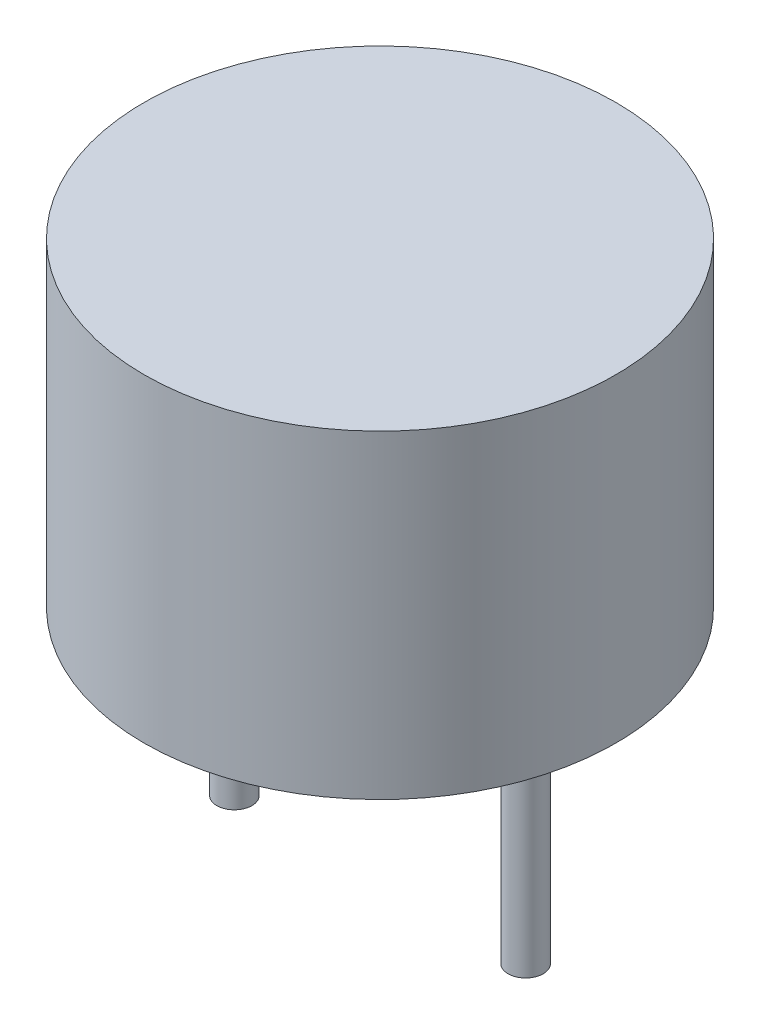
SolidWorks part; units mm, degrees
ref_plane "Front Plane" through (0, 0, 0) normal (0, 0, 1) x (1, 0, 0)
ref_plane "Top Plane" through (0, 0, 0) normal (0, 1, 0) x (1, 0, 0)
ref_plane "Right Plane" through (0, 0, 0) normal (1, 0, 0) x (0, 0, -1)
sketch "Sketch1" plane through (0, 0, 0) normal (0, 1, 0) x (1, 0, 0)
  circle A0 centre (0, 0) radius 6.5722
  dimension "D1" = 13.1445
extrude "Boss-Extrude1" add sketch "Sketch1" along normal blind 8.89
sketch "Sketch2" plane through (0, 0, 0) normal (0, -1, 0) x (1, 0, 0)
  circle A0 centre (-4.0577, 0) radius 0.489
  circle A1 centre (4.0577, 0) radius 0.489
  dimension "D1" = 0.9779
  dimension "D2" = 0.9779
  dimension "D3" = 4.0577
  dimension "D4" = 4.0577
extrude "Boss-Extrude2" add sketch "Sketch2" along normal blind 6.5786
